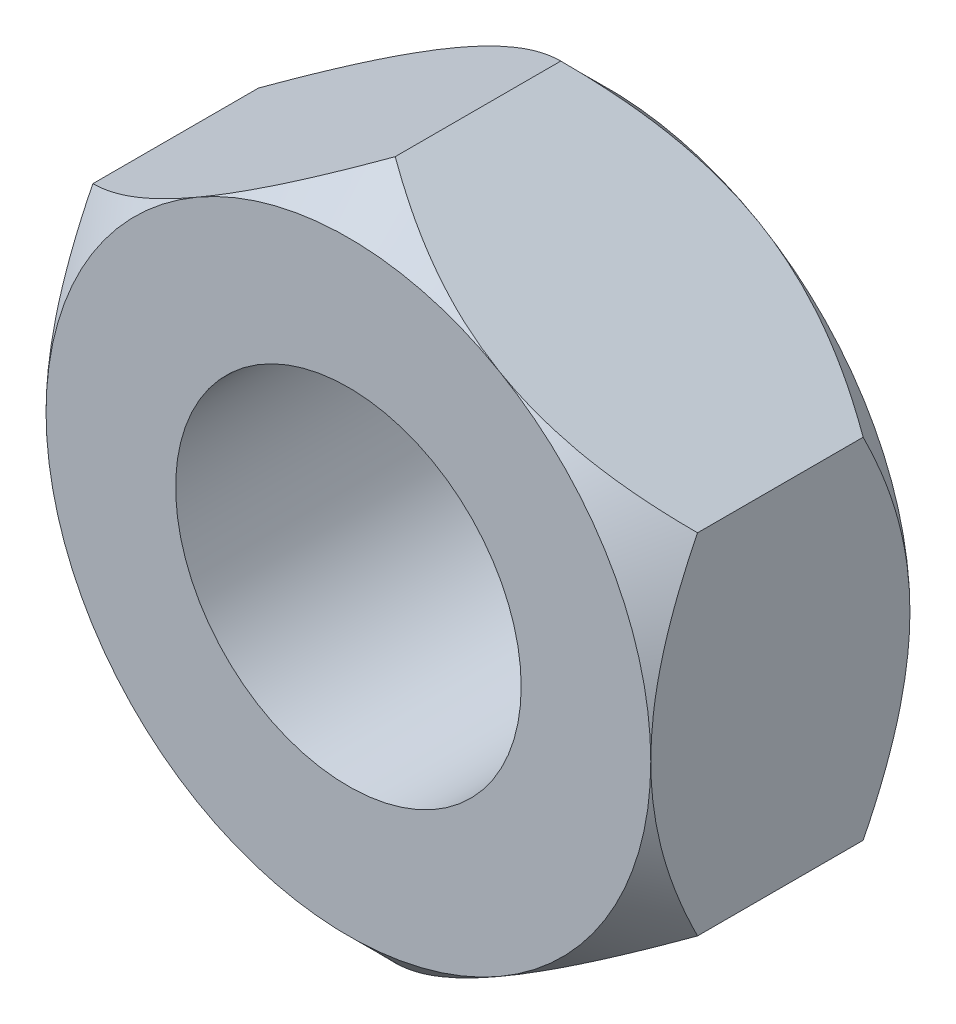
SolidWorks part; units mm, degrees
ref_plane "Front Plane" through (0, 0, 0) normal (0, 0, 1) x (1, 0, 0)
ref_plane "Top Plane" through (0, 0, 0) normal (0, 1, 0) x (1, 0, 0)
ref_plane "Right Plane" through (0, 0, 0) normal (1, 0, 0) x (0, 0, -1)
sketch "Sketch1" plane through (0, 0, 0) normal (0, 0, 1) x (1, 0, 0)
  line L1 (3.5, 2.0207) -> (0, 4.0415)
  line L2 (0, 4.0415) -> (-3.5, 2.0207)
  line L3 (-3.5, 2.0207) -> (-3.5, -2.0207)
  line L4 (-3.5, -2.0207) -> (0, -4.0415)
  line L5 (0, -4.0415) -> (3.5, -2.0207)
  line L6 (3.5, -2.0207) -> (3.5, 2.0207)
  circle A0 centre (0, 0) radius 3.5 construction
  circle A1 centre (0, 0) radius 2
  dimension "D2" = 4
  dimension "D1" = 7
extrude "Boss-Extrude1" add sketch "Sketch1" along normal blind 3
sketch "Sketch2" plane through (0, 0, 3) normal (0, 0, 1) x (1, 0, 0)
  circle A0 centre (0, 0) radius 3.5
extrude "Cut-Extrude1" cut sketch "Sketch2" against normal blind 3 draft 45 flip side to cut
ref_plane "Plane1" through (0, 0, 1.5) normal (0, 0, -1) x (-1, 0, 0)
mirror "Mirror1" about plane through (0, 0, 1.5) normal (0, 0, -1) of "Cut-Extrude1"
sketch "Sketch3" plane through (0, 0, 0) normal (0, 0, -1) x (-1, 0, 0)
  line L0 (0, 0) -> (6.5448, 0)
